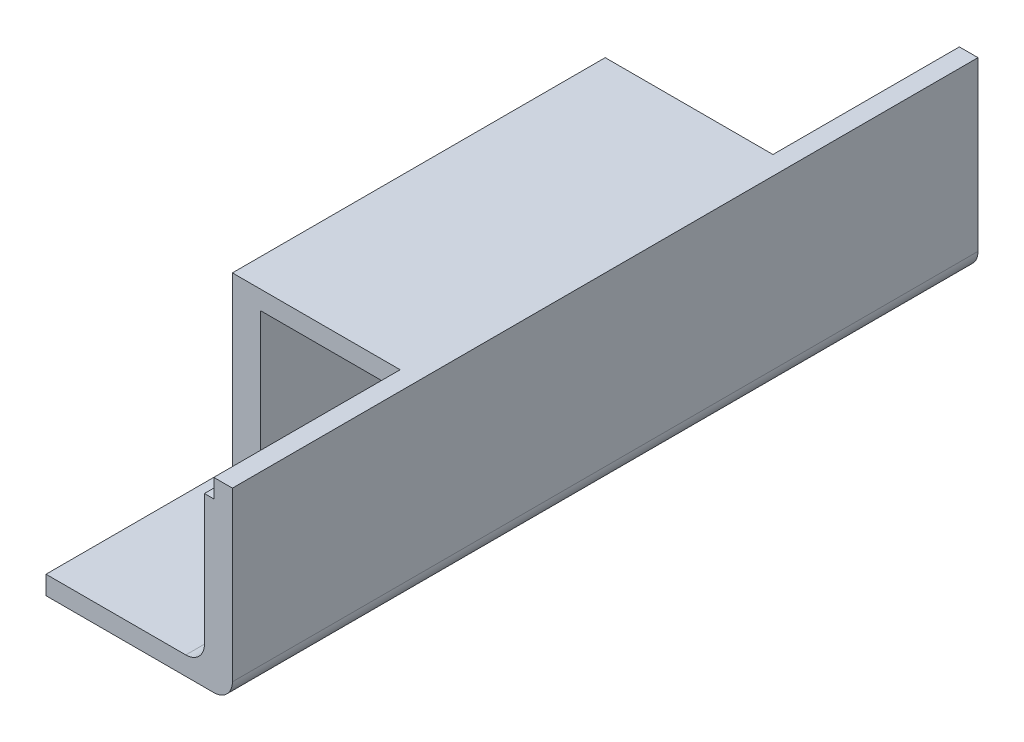
SolidWorks part; units mm, degrees
ref_plane "Alzado" through (0, 0, 0) normal (0, 0, 1) x (1, 0, 0)
ref_plane "Planta" through (0, 0, 0) normal (0, 1, 0) x (1, 0, 0)
ref_plane "Vista lateral" through (0, 0, 0) normal (1, 0, 0) x (0, 0, -1)
sketch "Croquis1" plane through (0, 0, 0) normal (0, 1, 0) x (1, 0, 0)
  line L6 (10, -40) -> (-10, -40)
  line L10 (10, -40) -> (10, 40)
  line L11 (10, 40) -> (-10, 40)
  line L12 (-10, -40) -> (-10, 40)
  line L13 (10, -40) -> (-10, 40) construction
  line L14 (10, 40) -> (-10, -40) construction
  point P0 (0, 0)
  dimension "D1" = 80
  dimension "D2" = 20
extrude "Saliente-Extruir1" add sketch "Croquis1" along normal blind 2
sketch "Croquis2" plane through (0, 2, 0) normal (0, 1, 0) x (1, 0, 0)
  line L0 (-10, -40) -> (10, -40) construction
  line L1 (10, 40) -> (7, 40)
  line L2 (10, 40) -> (10, -40)
  line L3 (10, -40) -> (7, -40)
  line L4 (7, 40) -> (7, -40)
  dimension "D1" = 3
extrude "Saliente-Extruir2" add sketch "Croquis2" along normal blind 16
fillet "Redondeo1" radius 2 1 edges at (10, 0, 0)
fillet "Redondeo2" radius 2 1 edges at (7, 2, 0)
sketch "Croquis3" plane through (0, 18, 0) normal (0, 1, 0) x (1, 0, 0)
  line L0 (10, -40) -> (10, 40) construction
  line L1 (10, 40) -> (-10, 40)
  line L2 (10, 40) -> (10, -40)
  line L3 (10, -40) -> (-10, -40)
  line L4 (-10, 40) -> (-10, -40)
  line L5 (5, 40) -> (-10, 40) construction
  line L6 (-10, 40) -> (-10, -40) construction
  point P6 (-10, 0)
extrude "Saliente-Extruir3" add sketch "Croquis3" along normal blind 2
sketch "Croquis5" plane through (0, 2, 0) normal (0, 1, 0) x (1, 0, 0)
  circle A0 centre (0, 30) radius 2.1
  circle A1 centre (0, -30) radius 2.1
  point P4 (0, 0)
  point P6 (0, 30)
  point P7 (7.0315, -29.1643)
  dimension "D3" = 4.2
  dimension "D4" = 4.2
  dimension "D1" = 60
  dimension "D2" = 30
extrude "Cortar-Extruir1" cut sketch "Croquis5" against normal blind 2
sketch "Croquis6" plane through (0, 20, 0) normal (0, 1, 0) x (1, 0, 0)
  line L5 (8, 40) -> (8, -40) construction
  line L10 (-10, 40) -> (8, 40)
  line L11 (-10, 40) -> (-10, 20)
  line L12 (-10, 20) -> (8, 20)
  line L13 (8, 40) -> (8, 20)
  line L16 (-10, -40) -> (8, -40)
  line L17 (-10, -40) -> (-10, -20)
  line L18 (-10, -20) -> (8, -20)
  line L19 (8, -40) -> (8, -20)
  dimension "D1" = 20
  dimension "D2" = 20
extrude "Cortar-Extruir3" cut sketch "Croquis6" against normal blind 2
sketch "Croquis7" plane through (0, 2, 0) normal (0, 1, 0) x (1, 0, 0)
  line L0 (8, -20) -> (-10, -20) construction
  line L1 (-10, 20) -> (-7, 20)
  line L2 (-10, 20) -> (-10, -20)
  line L3 (-10, -20) -> (-7, -20)
  line L4 (-7, 20) -> (-7, -20)
  dimension "D1" = 3
extrude "Saliente-Extruir4" add sketch "Croquis7" along normal up to vertex (16 mm away)
